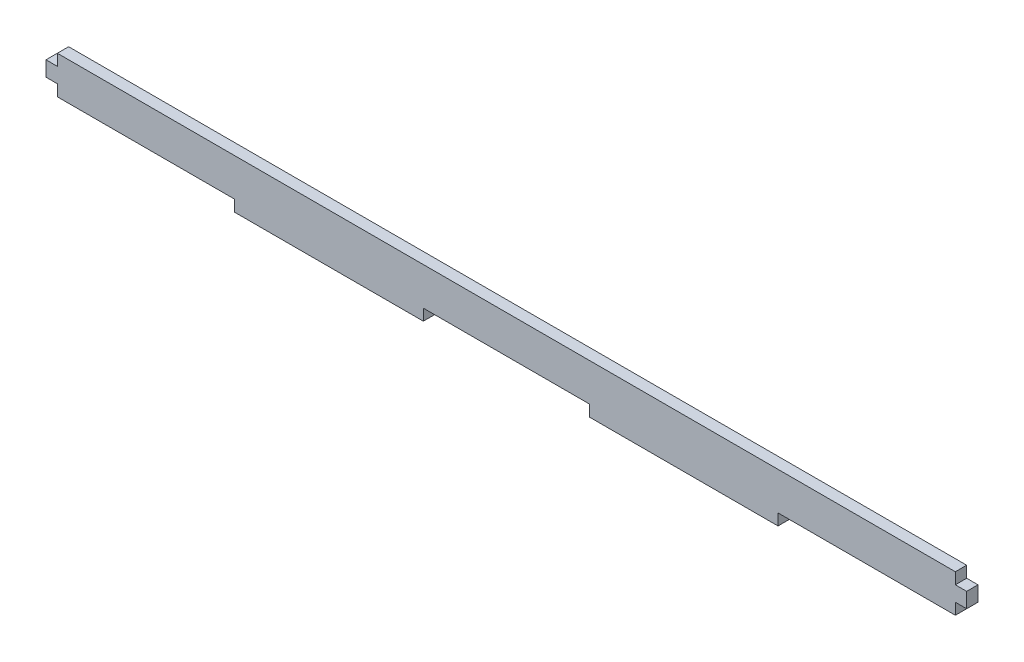
SolidWorks part; units mm, degrees
ref_plane "Front Plane" through (0, 0, 0) normal (0, 0, 1) x (1, 0, 0)
ref_plane "Top Plane" through (0, 0, 0) normal (0, 1, 0) x (1, 0, 0)
ref_plane "Right Plane" through (0, 0, 0) normal (1, 0, 0) x (0, 0, -1)
sketch "Sketch1" plane through (0, 0, 0) normal (0, 0, 1) x (1, 0, 0)
  line L0 (97, 0) -> (141, 0)
  line L1 (0, 0) -> (47, 0)
  line L2 (0, 0) -> (0, 3)
  line L3 (0, 10) -> (238, 10)
  line L4 (238, 0) -> (238, 3)
  line L5 (191, 0) -> (238, 0)
  line L6 (47, 0) -> (47, -3)
  line L7 (47, -3) -> (97, -3)
  line L8 (97, 0) -> (97, -3)
  line L9 (0, 7) -> (0, 10)
  line L10 (141, 0) -> (141, -3)
  line L11 (141, -3) -> (191, -3)
  line L12 (191, 0) -> (191, -3)
  line L13 (0, 7) -> (-3, 7)
  line L14 (238, 7) -> (238, 10)
  line L15 (0, 3) -> (-3, 3)
  line L16 (-3, 7) -> (-3, 3)
  line L17 (238, 7) -> (241, 7)
  line L19 (238, 3) -> (241, 3)
  line L20 (241, 7) -> (241, 3)
  dimension "D1" = 50
  dimension "D2" = 50
  dimension "D3" = 238
  dimension "D4" = 47
  dimension "D5" = 44
  dimension "D6" = 3
  dimension "D7" = 3
  dimension "D8" = 10
  dimension "D9" = 4
  dimension "D10" = 3
  dimension "D11" = 3
  dimension "D12" = 4
  dimension "D13" = 3
  dimension "D14" = 3
extrude "Boss-Extrude1" add sketch "Sketch1" along normal blind 3
